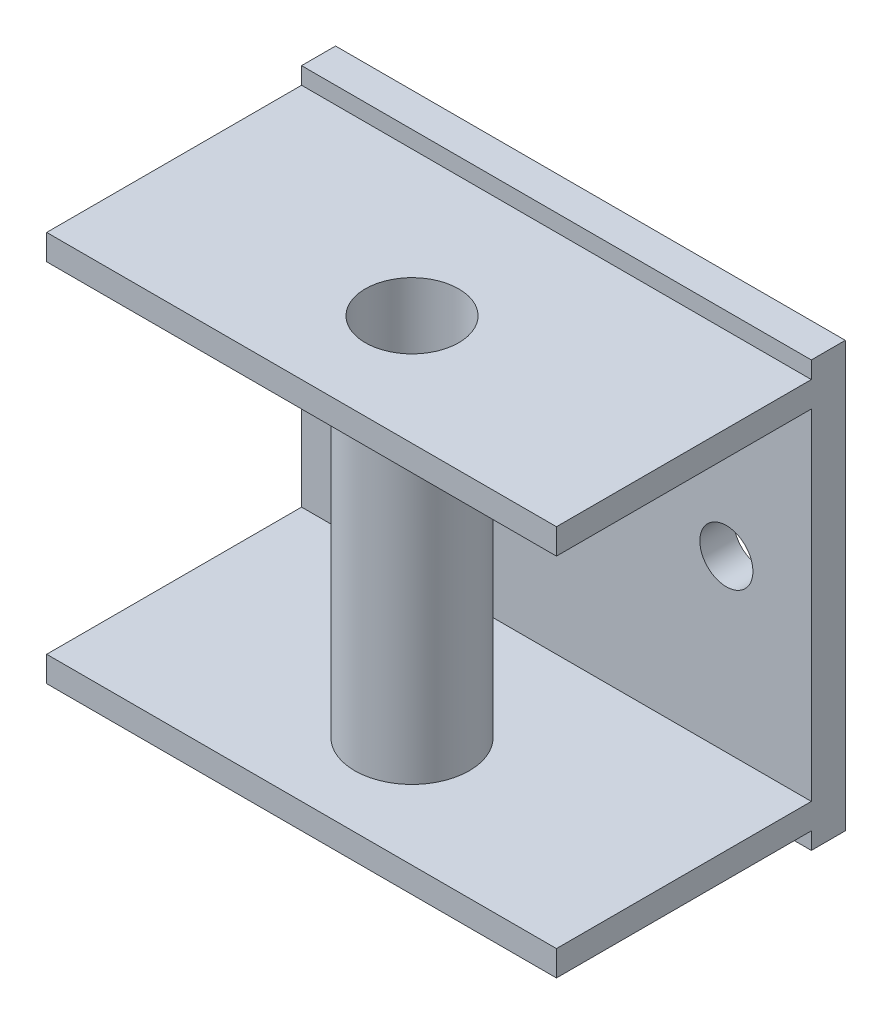
SolidWorks part; units mm, degrees
ref_plane "Спереди" through (0, 0, 0) normal (0, 0, 1) x (1, 0, 0)
ref_plane "Сверху" through (0, 0, 0) normal (0, 1, 0) x (1, 0, 0)
ref_plane "Справа" through (0, 0, 0) normal (1, 0, 0) x (0, 0, -1)
sketch "Эскиз1" plane through (0, 0, 0) normal (0, 0, 1) x (1, 0, 0)
  line L0 (0, 0) -> (0, 31.3463) construction
  line L1 (-60, -50) -> (60, -50)
  line L2 (-60, -50) -> (-60, 50)
  line L3 (-60, 50) -> (60, 50)
  line L4 (60, -50) -> (60, 50)
  line L5 (-60, -50) -> (60, 50) construction
  line L6 (-60, 50) -> (60, -50) construction
  circle A0 centre (0, 0) radius 6.25
  circle A1 centre (40, 0) radius 6.25
  circle A2 centre (-40, 0) radius 6.25
  point P0 (0, 0)
  point P12 (60, 0)
  dimension "D3" = 12.5
  dimension "D4" = 80
  dimension "D1" = 100
  dimension "D2" = 120
extrude "Бобышка-Вытянуть1" add sketch "Эскиз1" along normal blind 8
sketch "Эскиз2" plane through (0, 0, 8) normal (0, 0, 1) x (1, 0, 0)
  line L0 (-60, 0) -> (60, 0) construction
  line L1 (-60, 50) -> (-60, -50) construction
  line L2 (60, -50) -> (60, 50) construction
  line L3 (-60, -50) -> (60, -50) construction
  line L4 (-60, -46) -> (60, -46)
  line L5 (-60, -46) -> (-60, -40)
  line L6 (-60, -40) -> (60, -40)
  line L7 (60, -46) -> (60, -40)
  line L8 (60, 46) -> (60, 40)
  line L9 (-60, 40) -> (60, 40)
  line L10 (-60, 46) -> (-60, 40)
  line L11 (-60, 46) -> (60, 46)
  dimension "D1" = 4
  dimension "D2" = 6
extrude "Бобышка-Вытянуть2" add sketch "Эскиз2" along normal blind 60
sketch "Эскиз3" plane through (0, -46, 0) normal (0, -1, 0) x (1, 0, 0)
  line L0 (-60, 68) -> (60, 68) construction
  line L1 (60, 68) -> (60, 8) construction
  circle A0 centre (0, 42) radius 11
  dimension "D1" = 22
  dimension "D2" = 15
  dimension "D3" = 60
extrude "Вырез-Вытянуть1" cut sketch "Эскиз3" against normal through all
sketch "Эскиз4" plane through (0, 40, 0) normal (0, -1, 0) x (1, 0, 0)
  circle A0 centre (0, 42) radius 13.5
  circle A1 centre (0, 42) radius 11
  dimension "D1" = 27
  dimension "D2" = 22
extrude "Бобышка-Вытянуть3" add sketch "Эскиз4" along normal up to next
